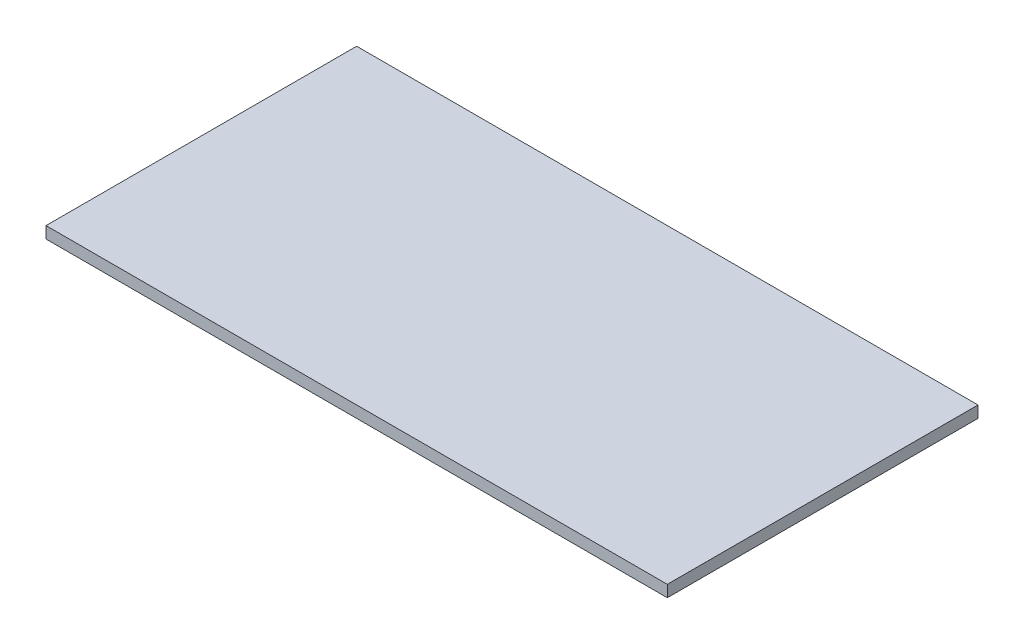
SolidWorks part; units mm, degrees
ref_plane "Front Plane" through (0, 0, 0) normal (0, 0, 1) x (1, 0, 0)
ref_plane "Top Plane" through (0, 0, 0) normal (0, 1, 0) x (1, 0, 0)
ref_plane "Right Plane" through (0, 0, 0) normal (1, 0, 0) x (0, 0, -1)
sketch "Sketch1" plane through (0, 0, 0) normal (0, 1, 0) x (1, 0, 0)
  line L1 (0, 0) -> (80, 0)
  line L2 (0, 0) -> (0, 40)
  line L3 (0, 40) -> (80, 40)
  line L4 (80, 0) -> (80, 40)
  dimension "D1" = 40
  dimension "D2" = 80
extrude "Boss-Extrude1" add sketch "Sketch1" along normal blind 1.5
